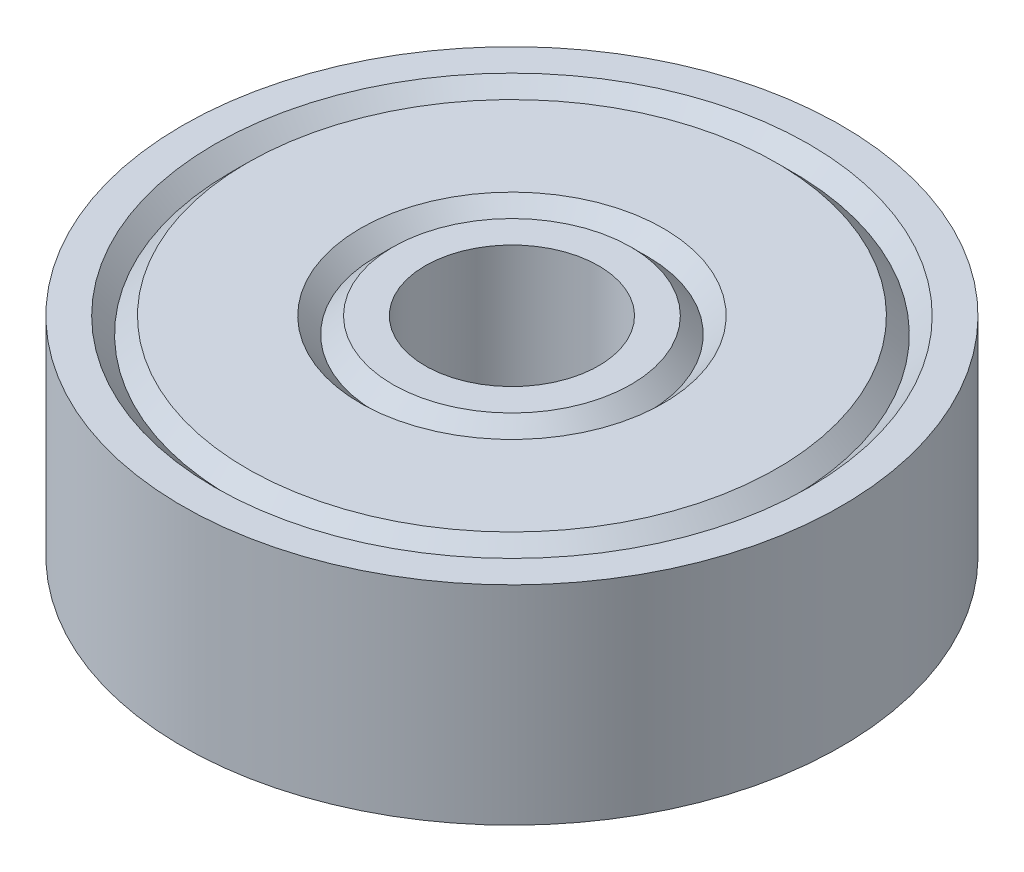
SolidWorks part; units mm, degrees
ref_plane "Front Plane" through (0, 0, 0) normal (0, 0, 1) x (1, 0, 0)
ref_plane "Top Plane" through (0, 0, 0) normal (0, 1, 0) x (1, 0, 0)
ref_plane "Right Plane" through (0, 0, 0) normal (1, 0, 0) x (0, 0, -1)
sketch "Sketch1" plane through (0, 0, 0) normal (0, 0, 1) x (1, 0, 0)
  line L0 (0, 3) -> (0, -3) construction
  line L1 (-2.5, 3) -> (-3.4333, 3)
  line L2 (-2.5, 3) -> (-2.5, -3)
  line L3 (-2.5, -3) -> (-3.4333, -3)
  line L4 (-9.5, 3) -> (-9.5, -3)
  line L5 (-8.5667, 3) -> (-8.1, 2.5333)
  line L6 (-8.1, 2.5333) -> (-7.6333, 3)
  line L7 (-4.3667, 3) -> (-3.9, 2.5333)
  line L8 (-3.9, 2.5333) -> (-3.4333, 3)
  line L9 (-8.5667, -3) -> (-8.1, -2.5333)
  line L10 (-8.1, -2.5333) -> (-7.6333, -3)
  line L11 (-4.3667, -3) -> (-3.9, -2.5333)
  line L12 (-3.9, -2.5333) -> (-3.4333, -3)
  line L13 (-4.3667, -3) -> (-7.6333, -3)
  line L14 (-8.5667, -3) -> (-9.5, -3)
  line L15 (-8.5667, 3) -> (-9.5, 3)
  line L16 (-4.3667, 3) -> (-7.6333, 3)
  line L17 (-8.1, 2.5333) -> (-3.9, 2.5333) construction
  line L18 (-8.1, 2.5333) -> (-8.1, -2.5333) construction
  line L19 (-3.9, -2.5333) -> (-8.1, -2.5333) construction
  line L20 (-3.9, 2.5333) -> (-3.9, -2.5333) construction
  line L21 (-8.1, 0) -> (-6.7, 0) construction
  line L22 (-3.4333, 3) -> (-4.3667, 3) construction
  line L23 (-6.7, 0) -> (-5.3, 0) construction
  line L24 (-8.1, 0) -> (-9.5, 0) construction
  line L25 (-5.3, 0) -> (-3.9, 0) construction
  line L26 (-3.9, 0) -> (-2.5, 0) construction
  dimension "D1" = 6
  dimension "D2" = 5
  dimension "D3" = 19
revolve "Revolve1" add sketch "Sketch1" angle 360 about L0
